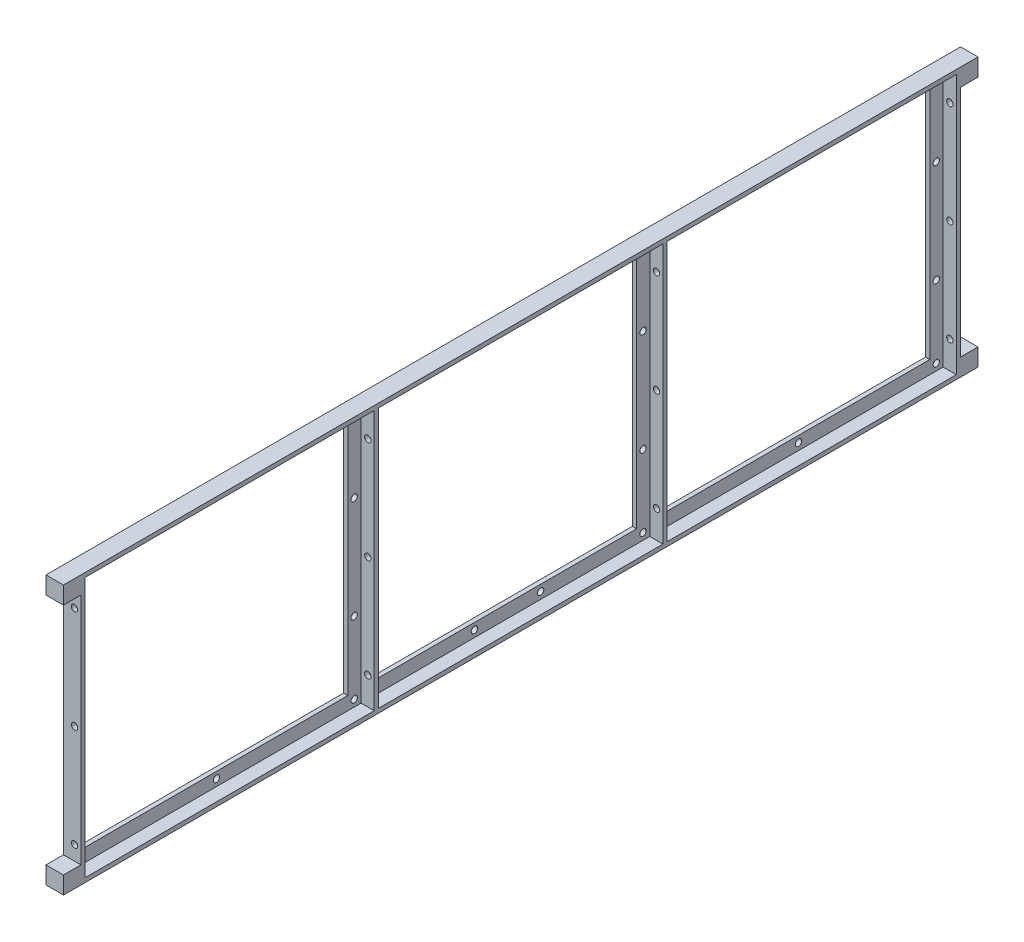
SolidWorks part; units mm, degrees
material "7075-O (SS)"
ref_plane "Front Plane" through (0, 0, 0) normal (0, 0, 1) x (1, 0, 0)
ref_plane "Top Plane" through (0, 0, 0) normal (0, 1, 0) x (1, 0, 0)
ref_plane "Right Plane" through (0, 0, 0) normal (1, 0, 0) x (0, 0, -1)
sketch "Sketch2" plane through (0, 0, 0) normal (0, 0, 1) x (1, 0, 0)
  line L0 (0, -55) -> (0, 55) construction
  line L1 (0, 0) -> (6.5, 0)
  line L2 (0, 0) -> (0, 6.5)
  line L3 (0, 6.5) -> (6.5, 6.5)
  line L4 (6.5, 0) -> (6.5, 6.5)
  line L5 (0, 100) -> (6.5, 100)
  line L6 (0, 100) -> (0, 93.5)
  line L7 (0, 93.5) -> (6.5, 93.5)
  line L8 (6.5, 100) -> (6.5, 93.5)
  dimension "D1" = 6.5
  dimension "D2" = 6.5
  dimension "D3" = 6.5
  dimension "D4" = 6.5
  dimension "D5" = 100
extrude "rails" add sketch "Sketch2" against normal blind 340.5
ref_plane "y midplane" through (0, 50, 0) normal (0, 1, 0) x (1, 0, 0)
ref_plane "front rail offset" through (0, 0, -6.5) normal (0, 0, 1) x (1, 0, 0)
ref_plane "back rail offset" through (0, 0, -334) normal (0, 0, 1) x (1, 0, 0)
ref_plane "z midplane" through (0, 0, -170.25) normal (0, 0, 1) x (1, 0, 0)
ref_plane "front segment separator" through (0, 0, -116.5) normal (0, 0, 1) x (1, 0, 0)
ref_plane "back segment separator" through (0, 0, -224) normal (0, 0, 1) x (1, 0, 0)
sketch "Sketch3" plane through (0, 0, -6.5) normal (0, 0, 1) x (1, 0, 0)
  line L0 (6.5, 6.5) -> (0, 6.5) construction
  line L1 (0, 93.5) -> (6.5, 93.5)
  line L2 (0, 93.5) -> (0, 6.5)
  line L3 (0, 6.5) -> (6.5, 6.5)
  line L4 (6.5, 93.5) -> (6.5, 6.5)
extrude "front strut" add sketch "Sketch3" against normal blind 1.5875
sketch "Sketch4" plane through (0, 0, -116.5) normal (0, 0, 1) x (1, 0, 0)
  line L1 (0, 93.5) -> (6.5, 93.5)
  line L2 (0, 93.5) -> (0, 6.5)
  line L3 (0, 6.5) -> (6.5, 6.5)
  line L4 (6.5, 93.5) -> (6.5, 6.5)
sketch "Sketch5" plane through (0, 0, -224) normal (0, 0, 1) x (1, 0, 0)
  line L1 (0, 93.5) -> (6.5, 93.5)
  line L2 (0, 93.5) -> (0, 6.5)
  line L3 (0, 6.5) -> (6.5, 6.5)
  line L4 (6.5, 93.5) -> (6.5, 6.5)
sketch "Sketch6" plane through (0, 0, -334) normal (0, 0, 1) x (1, 0, 0)
  line L1 (0, 93.5) -> (6.5, 93.5)
  line L2 (0, 93.5) -> (0, 6.5)
  line L3 (0, 6.5) -> (6.5, 6.5)
  line L4 (6.5, 93.5) -> (6.5, 6.5)
extrude "front mid strut" add sketch "Sketch4" along normal mid plane 1.5875
extrude "back mid strut" add sketch "Sketch5" along normal mid plane 1.5875
extrude "back strut" add sketch "Sketch6" along normal blind 1.5875 contours L4 L3 L2 L1
sketch "Sketch7" plane through (0, 0, 0) normal (1, 0, 0) x (0, 0, -1)
  line L0 (115.7062, 6.5) -> (8.0875, 6.5) construction
  line L1 (8.0875, 93.5) -> (13, 93.5)
  line L2 (8.0875, 93.5) -> (8.0875, 6.5)
  line L3 (8.0875, 6.5) -> (13, 6.5)
  line L4 (13, 93.5) -> (13, 6.5)
  line L5 (110.7937, 93.5) -> (115.7062, 93.5)
  line L6 (110.7937, 93.5) -> (110.7937, 6.5)
  line L7 (110.7937, 6.5) -> (115.7062, 6.5)
  line L8 (115.7062, 93.5) -> (115.7062, 6.5)
  line L9 (117.2937, 93.5) -> (122.2062, 93.5)
  line L10 (117.2937, 93.5) -> (117.2937, 6.5)
  line L11 (117.2937, 6.5) -> (122.2062, 6.5)
  line L12 (122.2062, 93.5) -> (122.2062, 6.5)
  line L13 (218.2938, 93.5) -> (223.2063, 93.5)
  line L14 (218.2938, 93.5) -> (218.2938, 6.5)
  line L15 (218.2938, 6.5) -> (223.2063, 6.5)
  line L16 (223.2063, 93.5) -> (223.2063, 6.5)
  line L17 (224.7938, 93.5) -> (229.7063, 93.5)
  line L18 (224.7938, 93.5) -> (224.7938, 6.5)
  line L19 (224.7938, 6.5) -> (229.7063, 6.5)
  line L20 (229.7063, 93.5) -> (229.7063, 6.5)
  line L21 (327.5, 93.5) -> (332.4125, 93.5)
  line L22 (327.5, 93.5) -> (327.5, 6.5)
  line L23 (327.5, 6.5) -> (332.4125, 6.5)
  line L24 (332.4125, 93.5) -> (332.4125, 6.5)
  line L25 (223.2063, 6.5) -> (117.2937, 6.5) construction
  line L26 (332.4125, 6.5) -> (224.7938, 6.5) construction
  dimension "D1" = 4.9125
  dimension "D2" = 4.9125
  dimension "D3" = 4.9125
  dimension "D4" = 4.9125
  dimension "D5" = 4.9125
  dimension "D6" = 4.9125
extrude "x side flanges" add sketch "Sketch7" along normal blind 1.5875
sketch "Sketch8" plane through (6.5, 0, 0) normal (1, 0, 0) x (0, 0, -1)
  line L0 (8.0875, 1.5875) -> (115.7062, 1.5875)
  line L1 (8.0875, 93.5) -> (115.7062, 93.5)
  line L2 (8.0875, 93.5) -> (8.0875, 98.4125)
  line L3 (8.0875, 98.4125) -> (115.7062, 98.4125)
  line L4 (115.7062, 93.5) -> (115.7062, 98.4125)
  line L5 (8.0875, 1.5875) -> (8.0875, 6.5)
  line L6 (8.0875, 6.5) -> (115.7062, 6.5)
  line L7 (115.7062, 1.5875) -> (115.7062, 6.5)
  line L16 (117.2937, 93.5) -> (223.2063, 93.5)
  line L17 (117.2937, 93.5) -> (117.2937, 98.4125)
  line L18 (117.2937, 98.4125) -> (223.2063, 98.4125)
  line L19 (223.2063, 93.5) -> (223.2063, 98.4125)
  line L20 (117.2937, 1.5875) -> (223.2063, 1.5875)
  line L21 (117.2937, 1.5875) -> (117.2937, 6.5)
  line L22 (117.2937, 6.5) -> (223.2063, 6.5)
  line L23 (223.2063, 1.5875) -> (223.2063, 6.5)
  line L32 (224.7938, 1.5875) -> (332.4125, 1.5875)
  line L33 (224.7938, 1.5875) -> (224.7938, 6.5)
  line L34 (224.7938, 6.5) -> (332.4125, 6.5)
  line L35 (332.4125, 1.5875) -> (332.4125, 6.5)
  line L36 (224.7938, 93.5) -> (332.4125, 93.5)
  line L37 (224.7938, 93.5) -> (224.7938, 98.4125)
  line L38 (224.7938, 98.4125) -> (332.4125, 98.4125)
  line L39 (332.4125, 93.5) -> (332.4125, 98.4125)
  line L48 (122.2062, 93.5) -> (117.2937, 93.5) construction
  line L50 (115.7062, 93.5) -> (8.0875, 93.5) construction
  line L51 (115.7062, 6.5) -> (115.7062, 93.5) construction
  dimension "D2" = 4.9125
  dimension "D4" = 4.9125
  dimension "D10" = 4.9125
  dimension "D12" = 4.9125
  dimension "D18" = 4.9125
  dimension "D20" = 4.9125
extrude "frame inserts" cut sketch "Sketch8" against normal blind 4.9125
sketch "Sketch9" plane through (0, 0, -6.5) normal (0, 0, 1) x (1, 0, 0)
  line L5 (3.575, 50) -> (-3.575, 50) construction
  line L6 (6.5, 6.5) -> (6.5, 93.5) construction
  circle A0 centre (4.1187, 88.1) radius 1.1906
  circle A1 centre (4.1187, 50) radius 1.1906
  circle A2 centre (4.1187, 11.9) radius 1.1906
  dimension "D1" = 2.3813
  dimension "D2" = 2.3813
  dimension "D3" = 2.3813
  dimension "D4" = 2.3813
  dimension "D5" = 38.1
  dimension "D6" = 38.1
extrude "z screwholes" cut sketch "Sketch9" against normal through all
sketch "Sketch10" plane through (0, 0, 0) normal (1, 0, 0) x (0, 0, -1)
  line L6 (13, 6.5) -> (13, 93.5) construction
  line L9 (13, 93.5) -> (110.7937, 93.5) construction
  line L11 (110.7937, 93.5) -> (110.7937, 6.5) construction
  line L12 (10.6188, 95.8812) -> (113.175, 95.8812) construction
  line L13 (122.2062, 6.5) -> (122.2062, 93.5) construction
  line L14 (122.2062, 93.5) -> (218.2938, 93.5) construction
  line L15 (3.575, 50) -> (-3.575, 50) construction
  line L16 (170.25, 155) -> (170.25, 45) construction
  line L17 (329.8813, 95.8812) -> (227.325, 95.8812) construction
  line L18 (329.8813, 4.1188) -> (227.325, 4.1188) construction
  line L19 (10.6188, 4.1188) -> (113.175, 4.1188) construction
  circle A0 centre (10.6188, 95.8812) radius 1.1906
  circle A32 centre (113.175, 95.8812) radius 1.1906
  circle A33 centre (61.8969, 95.8812) radius 1.1906
  circle A34 centre (119.825, 95.8812) radius 1.1906
  circle A35 centre (157.925, 95.8812) radius 1.1906
  circle A36 centre (10.6188, 69.05) radius 1.1906
  circle A37 centre (113.175, 69.05) radius 1.1906
  circle A38 centre (119.825, 69.05) radius 1.1906
  circle A39 centre (220.675, 69.05) radius 1.1906
  circle A40 centre (227.325, 69.05) radius 1.1906
  circle A41 centre (329.8813, 69.05) radius 1.1906
  circle A42 centre (182.575, 95.8812) radius 1.1906
  circle A43 centre (220.675, 95.8812) radius 1.1906
  circle A44 centre (278.6031, 95.8812) radius 1.1906
  circle A45 centre (227.325, 95.8812) radius 1.1906
  circle A46 centre (329.8813, 95.8812) radius 1.1906
  circle A47 centre (329.8813, 4.1188) radius 1.1906
  circle A48 centre (227.325, 4.1188) radius 1.1906
  circle A49 centre (278.6031, 4.1188) radius 1.1906
  circle A50 centre (220.675, 4.1188) radius 1.1906
  circle A51 centre (182.575, 4.1188) radius 1.1906
  circle A52 centre (329.8813, 30.95) radius 1.1906
  circle A53 centre (227.325, 30.95) radius 1.1906
  circle A54 centre (220.675, 30.95) radius 1.1906
  circle A55 centre (119.825, 30.95) radius 1.1906
  circle A56 centre (113.175, 30.95) radius 1.1906
  circle A57 centre (10.6188, 30.95) radius 1.1906
  circle A58 centre (157.925, 4.1188) radius 1.1906
  circle A59 centre (119.825, 4.1188) radius 1.1906
  circle A60 centre (61.8969, 4.1188) radius 1.1906
  circle A61 centre (113.175, 4.1188) radius 1.1906
  circle A62 centre (10.6188, 4.1188) radius 1.1906
  point P8 (61.8969, 95.8812)
  dimension "D1" = 2.3813
  dimension "D3" = 2.3813
  dimension "D5" = 2.3813
  dimension "D6" = 2.3813
  dimension "D9" = 2.3813
  dimension "D10" = 38.1
  dimension "D7" = 2.3813
  dimension "D11" = 2.3813
  dimension "D12" = 2.3813
  dimension "D15" = 2.3813
  dimension "D2" = 2.3813
  dimension "D4" = 2.3813
  dimension "D8" = 2.3813
  dimension "D13" = 2.3813
  dimension "D14" = 19.05
extrude "x screwholes" cut sketch "Sketch10" along normal through all
